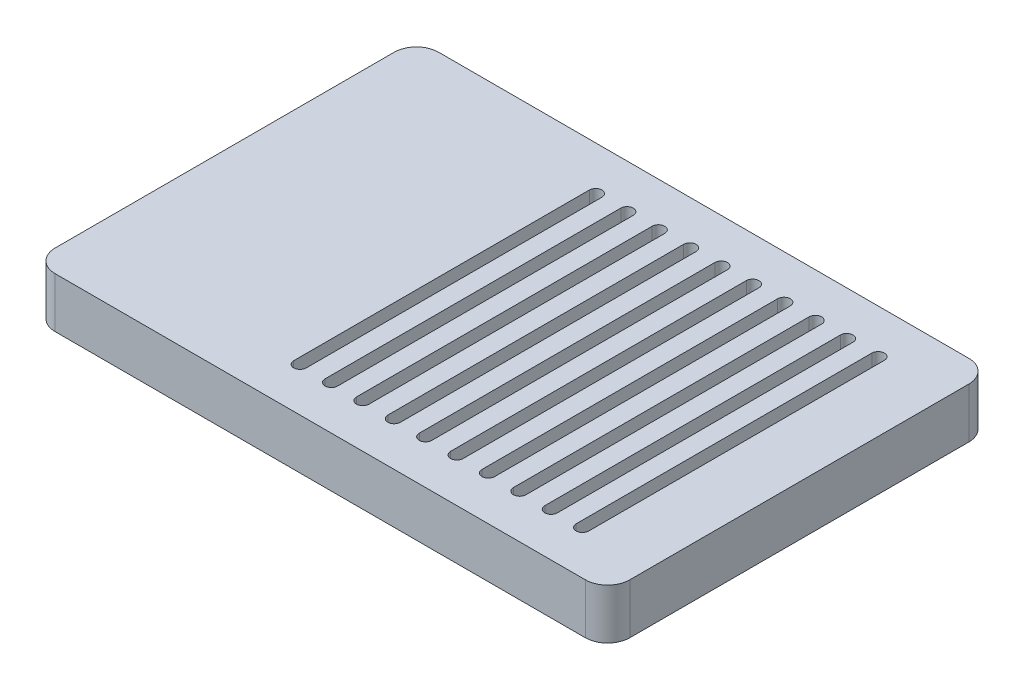
SolidWorks part; units mm, degrees
material "Custom Plastic"
ref_plane "Спереди" through (0, 0, 0) normal (0, 0, 1) x (1, 0, 0)
ref_plane "Сверху" through (0, 0, 0) normal (0, 1, 0) x (1, 0, 0)
ref_plane "Справа" through (0, 0, 0) normal (1, 0, 0) x (0, 0, -1)
ref_plane "Plane1" through (0, 22.1, 0) normal (0, 1, 0) x (1, 0, 0)
sketch "Sketch1" plane through (0, 22.1, -139.3737) normal (0, 1, 0) x (1, 0, 0)
  line L0 (46.5, -162.24) -> (46.5, -101.14)
  line L1 (46.5, -101.14) -> (-45.05, -101.14)
  line L2 (-45.05, -101.14) -> (-45.05, -162.24)
  line L3 (-45.05, -162.24) -> (46.5, -162.24)
extrude "Boss-Extrude1" add sketch "Sketch1" against normal blind 8
sketch "Sketch2" plane through (0, 14.1, -139.3737) normal (0, -1, 0) x (1, 0, 0)
  line L0 (-44.05, 161.24) -> (-44.05, 102.14)
  line L1 (-44.05, 102.14) -> (45.5, 102.14)
  line L2 (45.5, 102.14) -> (45.5, 161.24)
  line L3 (45.5, 161.24) -> (-44.05, 161.24)
  line L4 (-45.05, 162.24) -> (46.5, 162.24) construction
  line L5 (-45.05, 101.14) -> (-45.05, 162.24) construction
  line L6 (46.5, 101.14) -> (-45.05, 101.14) construction
  line L7 (46.5, 162.24) -> (46.5, 101.14) construction
  dimension "D1" = 1
  dimension "D2" = 1
  dimension "D3" = 1
  dimension "D4" = 1
extrude "Cut-Extrude1" cut sketch "Sketch2" against normal blind 6
sketch "Sketch3" plane through (-45.05, 0, -139.3737) normal (-1, 0, 0) x (0, 0, 1)
  line L0 (157.5557, 14.1) -> (157.5557, 19.25)
  line L1 (157.5557, 19.25) -> (143.8557, 19.25)
  line L2 (143.8557, 19.25) -> (143.8557, 14.1)
  line L3 (143.8557, 14.1) -> (157.5557, 14.1)
extrude "Cut-Extrude2" cut sketch "Sketch3" against normal up to next
sketch "Sketch4" plane through (-45.05, 0, -139.3737) normal (-1, 0, 0) x (0, 0, 1)
  line L0 (139.1557, 14.1) -> (139.1557, 19.25)
  line L1 (139.1557, 19.25) -> (125.4557, 19.25)
  line L2 (125.4557, 19.25) -> (125.4557, 14.1)
  line L3 (125.4557, 14.1) -> (139.1557, 14.1)
extrude "Cut-Extrude3" cut sketch "Sketch4" against normal up to next
sketch "Sketch5" plane through (-45.05, 0, -139.3737) normal (-1, 0, 0) x (0, 0, 1)
  line L0 (106.7182, 14.1) -> (120.8912, 14.1)
  line L1 (118.9547, 15.6) -> (108.6547, 15.6)
  arc A0 (120.8912, 14.1) -> (118.9547, 15.6) centre (118.9547, 13.6) ccw
  arc A1 (108.6547, 15.6) -> (106.7182, 14.1) centre (108.6547, 13.6) ccw
extrude "Cut-Extrude4" cut sketch "Sketch5" against normal up to next
fillet "Fillet1" radius 2 8 edges at (-44.55, 19.25, 18.182) (-44.55, 19.25, 4.482) (45.5, 17.1, -37.2337) (45.5, 17.1, 21.8663) (-44.55, 19.25, -13.918) (-44.05, 17.1, -37.2337) (-44.55, 19.25, -0.218) (-44.05, 17.1, 21.8663)
fillet "Fillet2" radius 3.55 4 edges at (46.5, 18.1, -38.2337) (46.5, 18.1, 22.8663) (-45.05, 18.1, 22.8663) (-45.05, 18.1, -38.2337)
sketch "Sketch6" plane through (0, 22.1, 0) normal (0, 1, 0) x (1, 0, 0)
  line L0 (35.5, 31.2337) -> (35.5, -15.8663) construction
  line L1 (36.5, 31.2337) -> (36.5, -15.8663)
  line L2 (34.5, 31.2337) -> (34.5, -15.8663)
  line L3 (-41.5, -22.8663) -> (42.95, -22.8663) construction
  line L4 (42.95, 38.2337) -> (-41.5, 38.2337) construction
  line L5 (46.5, -19.3163) -> (46.5, 34.6837) construction
  arc A0 (36.5, 31.2337) -> (34.5, 31.2337) centre (35.5, 31.2337) ccw
  arc A1 (34.5, -15.8663) -> (36.5, -15.8663) centre (35.5, -15.8663) ccw
  point P2 (35.5, 7.6837)
  dimension "D1" = 7
  dimension "D2" = 7
  dimension "D3" = 10
  dimension "D4" = 2
extrude "Cut-Extrude5" cut sketch "Sketch6" against normal up to surface (2 mm away) up to face at (0.725, 20.1, -7.6837)
pattern_linear "LPattern1" count 10 spacing 5 along (-1, 0, 0) of "Cut-Extrude5"
